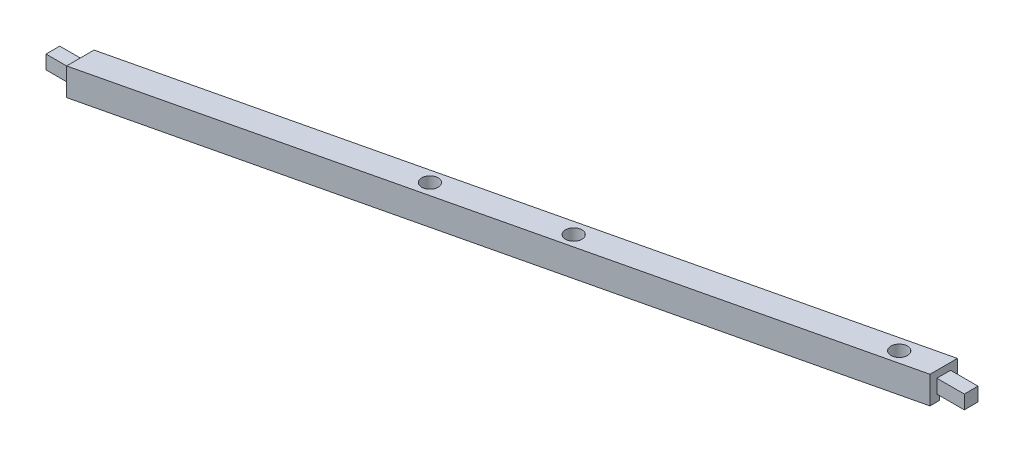
SolidWorks part; units mm, degrees
ref_plane "Front Plane" through (0, 0, 0) normal (0, 0, 1) x (1, 0, 0)
ref_plane "Top Plane" through (0, 0, 0) normal (0, 1, 0) x (1, 0, 0)
ref_plane "Right Plane" through (0, 0, 0) normal (1, 0, 0) x (0, 0, -1)
sketch "Sketch1" plane through (0, 0, 0) normal (0, 1, 0) x (1, 0, 0)
  line L0 (0, 0) -> (127.3, 30)
  line L1 (0, 0) -> (127.3, 0)
  line L2 (0, 0) -> (0, 35)
  line L3 (0, 35) -> (127.3, 35)
  line L4 (127.3, 0) -> (127.3, 35)
  line L5 (127.3, 35) -> (0, 5)
  dimension "D1" = 35
  dimension "D2" = 127.3
  dimension "D3" = 5
  dimension "D4" = 5
extrude "Boss-Extrude1" add sketch "Sketch1" along normal blind 5 contours L4 L5 L2 L0
sketch "Sketch2" plane through (127.3, 0, 0) normal (1, 0, 0) x (0, 0, -1)
  line L0 (30, 5) -> (30, 0) construction
  line L1 (31.25, 3.75) -> (33.75, 3.75)
  line L2 (31.25, 3.75) -> (31.25, 1.25)
  line L3 (31.25, 1.25) -> (33.75, 1.25)
  line L4 (33.75, 3.75) -> (33.75, 1.25)
  line L5 (30, 5) -> (35, 5) construction
  dimension "D1" = 2.5
  dimension "D2" = 2.5
  dimension "D3" = 1.25
  dimension "D4" = 1.25
extrude "Boss-Extrude2" add sketch "Sketch2" along normal blind 5
sketch "Sketch3" plane through (0, 0, 0) normal (-1, 0, 0) x (0, 0, 1)
  line L0 (0, 0) -> (-5, 0) construction
  line L1 (-3.75, 3.75) -> (-1.25, 3.75)
  line L2 (-3.75, 3.75) -> (-3.75, 1.25)
  line L3 (-3.75, 1.25) -> (-1.25, 1.25)
  line L4 (-1.25, 3.75) -> (-1.25, 1.25)
  line L5 (0, 5) -> (0, 0) construction
  dimension "D1" = 2.5
  dimension "D2" = 2.5
  dimension "D3" = 1.25
  dimension "D4" = 1.25
extrude "Boss-Extrude3" add sketch "Sketch3" along normal blind 5
sketch "Sketch6" plane through (0, 0, 0) normal (0, -1, 0) x (1, 0, 0)
  line L0 (0, 0) -> (127.3, -30) construction
  line L1 (0, 0) -> (0, -5) construction
  line L2 (127.3, -35) -> (0, -5) construction
  line L3 (127.3, -30) -> (127.3, -35) construction
  circle A0 centre (51.5, -14.7052) radius 1.5
  circle A1 centre (72.8, -19.5878) radius 1.5
  circle A2 centre (120.8, -30.8997) radius 1.5
  dimension "D1" = 3
  dimension "D2" = 2.5
  dimension "D3" = 51.5
  dimension "D4" = 3
  dimension "D5" = 2.5
  dimension "D6" = 6.5
  dimension "D7" = 48
  dimension "D8" = 2.5
  dimension "D9" = 3
extrude "Cut-Extrude1" cut sketch "Sketch6" against normal blind 5
sketch "Sketch7" plane through (0, 0, 0) normal (0, -1, 0) x (-1, 0, 0)
  line L0 (0, 3.25) -> (-127.3, 33.25)
  line L1 (0, 0) -> (0, 5) construction
  line L2 (-127.3, 30) -> (-127.3, 35) construction
  line L3 (0, 1.75) -> (-127.3, 31.75)
  line L4 (0, 3.25) -> (0, 1.75)
  line L5 (-127.3, 33.25) -> (-127.3, 31.75)
  dimension "D1" = 1.75
  dimension "D2" = 1.75
  dimension "D3" = 1.75
extrude "Cut-Extrude2" cut sketch "Sketch7" against normal blind 2
